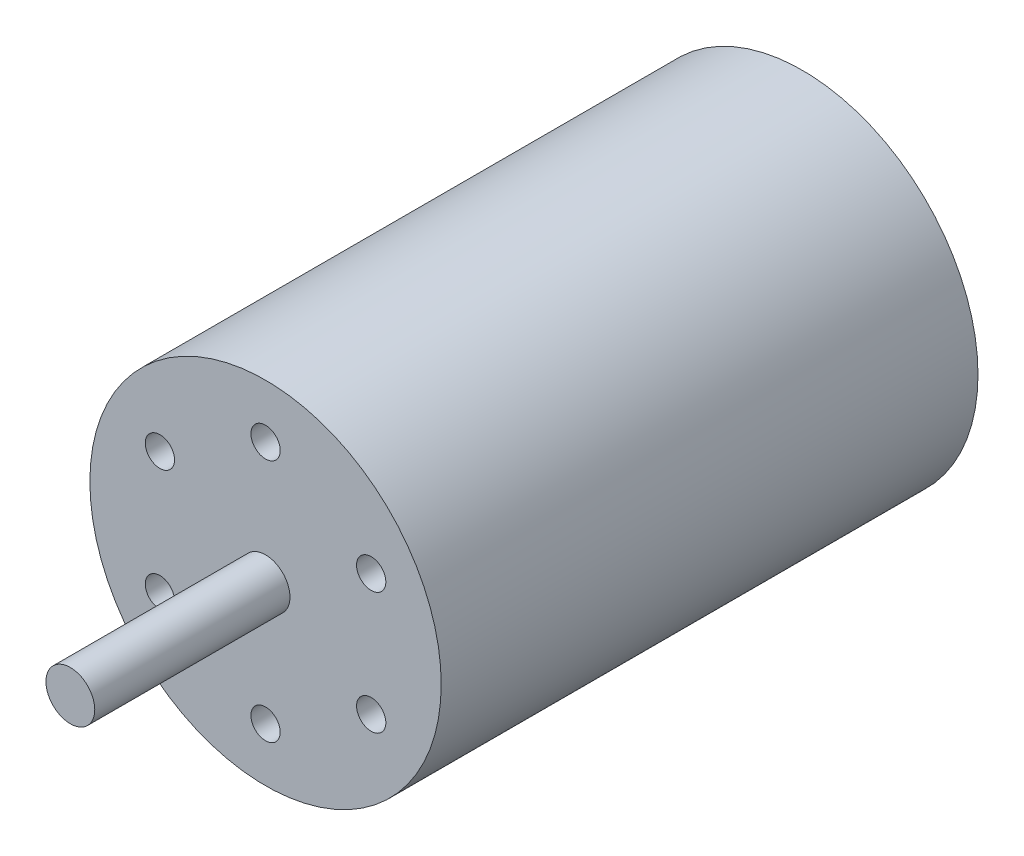
SolidWorks part; units mm, degrees
material "AISI 1020 Steel, Cold Rolled"
ref_plane "Front" through (0, 0, 0) normal (0, 0, 1) x (1, 0, 0)
ref_plane "Top" through (0, 0, 0) normal (0, 1, 0) x (1, 0, 0)
ref_plane "Right" through (0, 0, 0) normal (1, 0, 0) x (0, 0, -1)
sketch "Sketch1" plane through (0, 0, 0) normal (0, 0, 1) x (1, 0, 0)
  circle A0 centre (0, 0) radius 18
  dimension "D1" = 36
extrude "Boss-Extrude1" add sketch "Sketch1" along normal blind 55
sketch "Sketch2" plane through (0, 0, 55) normal (0, 0, 1) x (1, 0, 0)
  circle A0 centre (0, 0) radius 2.5
  dimension "D1" = 5
extrude "Boss-Extrude2" add sketch "Sketch2" along normal blind 20
sketch "Sketch3" plane through (0, 0, 55) normal (0, 0, 1) x (1, 0, 0)
  circle A0 centre (0, 0) radius 12.5 construction
  circle A1 centre (0, 12.5) radius 1.5
  circle A2 centre (10.8253, 6.25) radius 1.5
  circle A3 centre (10.8253, -6.25) radius 1.5
  circle A4 centre (0, -12.5) radius 1.5
  circle A5 centre (-10.8253, -6.25) radius 1.5
  circle A6 centre (-10.8253, 6.25) radius 1.5
  point P17 (0, 0)
  dimension "D1" = 6
extrude "Cut-Extrude1" cut sketch "Sketch3" against normal blind 10
